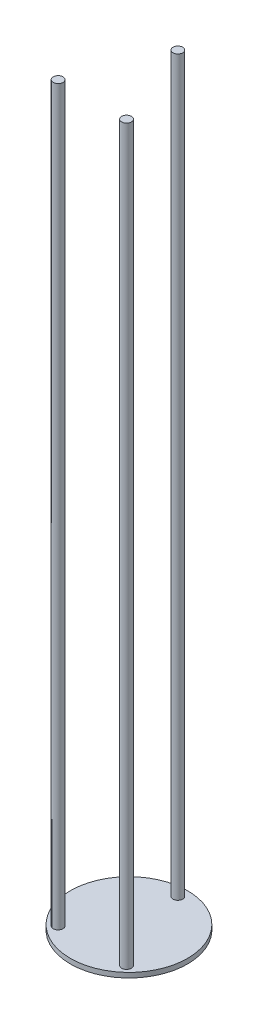
SolidWorks part; units mm, degrees
material "1060 Alloy"
ref_plane "Front Plane" through (0, 0, 0) normal (0, 0, 1) x (1, 0, 0)
ref_plane "Top Plane" through (0, 0, 0) normal (0, 1, 0) x (1, 0, 0)
ref_plane "Right Plane" through (0, 0, 0) normal (1, 0, 0) x (0, 0, -1)
sketch "Sketch1" plane through (0, 0, 0) normal (0, 1, 0) x (1, 0, 0)
  circle A0 centre (0, 0) radius 120
  dimension "D1" = 240
extrude "Boss-Extrude1" add sketch "Sketch1" along normal blind 10
sketch "Sketch2" plane through (0, 10, 0) normal (0, 1, 0) x (1, 0, 0)
  line L0 (0, -5.5) -> (0, 5.5) construction
  circle A0 centre (0, 100) radius 10
  circle A1 centre (-70, -75) radius 10
  circle A2 centre (0, 0) radius 120 construction
  circle A3 centre (70, -75) radius 10
  dimension "D4" = 20
  dimension "D5" = 20
  dimension "D1" = 75
  dimension "D2" = 70
  dimension "D3" = 100
  dimension "D6" = 175
extrude "Boss-Extrude2" add sketch "Sketch2" along normal blind 1500
